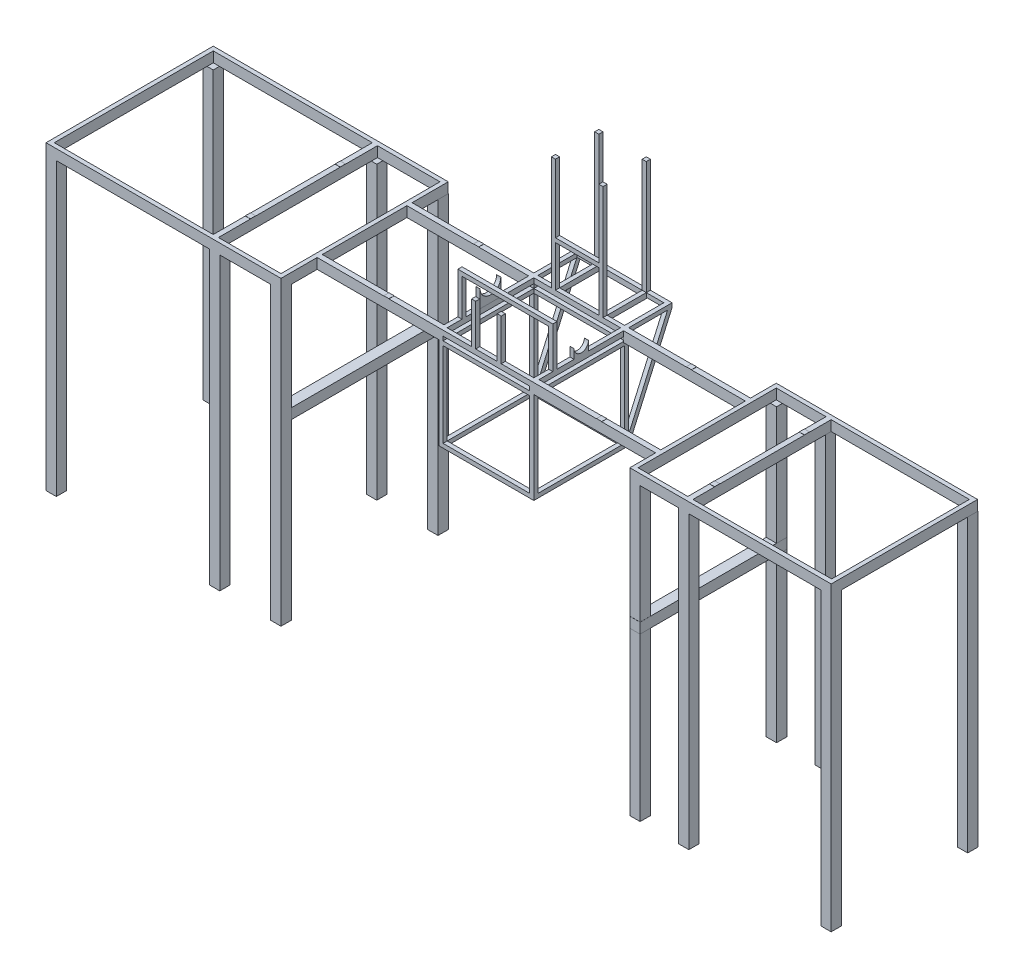
SolidWorks part; units mm, degrees
ref_plane "Front" through (0, 0, 0) normal (0, 0, 1) x (1, 0, 0)
ref_plane "Top" through (0, 0, 0) normal (0, 1, 0) x (1, 0, 0)
ref_plane "Right" through (0, 0, 0) normal (1, 0, 0) x (0, 0, -1)
sketch "Croquis1" plane through (0, 0, 0) normal (0, 1, 0) x (1, 0, 0)
  line L0 (20, 20) -> (440, 20)
  line L1 (0, 0) -> (460, 0)
  line L2 (0, 0) -> (0, 460)
  line L3 (0, 460) -> (460, 460)
  line L4 (460, 0) -> (460, 460)
  line L5 (440, 20) -> (440, 440)
  line L6 (20, 440) -> (440, 440)
  line L7 (20, 20) -> (20, 440)
  dimension "D1" = 20
  dimension "D2" = 420
extrude "Saliente-Extruir1" add sketch "Croquis1" along normal blind 25
sketch "Croquis2" plane through (0, 0, 0) normal (0, -1, 0) x (1, 0, 0)
  line L1 (0, 0) -> (20, 0)
  line L2 (0, 0) -> (0, -20)
  line L3 (0, -20) -> (20, -20)
  line L4 (20, 0) -> (20, -20)
  line L5 (0, -460) -> (20, -460)
  line L6 (0, -460) -> (0, -440)
  line L7 (0, -440) -> (20, -440)
  line L8 (20, -460) -> (20, -440)
  line L9 (460, -460) -> (440, -460)
  line L10 (460, -460) -> (460, -440)
  line L11 (460, -440) -> (440, -440)
  line L12 (440, -460) -> (440, -440)
  line L13 (460, 0) -> (440, 0)
  line L14 (460, 0) -> (460, -20)
  line L15 (460, -20) -> (440, -20)
  line L16 (440, 0) -> (440, -20)
extrude "Saliente-Extruir2" add sketch "Croquis2" along normal blind 20
sketch "Croquis3" plane through (0, -20, 0) normal (0, -1, 0) x (1, 0, 0)
  line L0 (20, -440) -> (20, -20)
  line L1 (0, -460) -> (460, -460)
  line L2 (0, -460) -> (0, 0)
  line L3 (0, 0) -> (460, 0)
  line L4 (460, -460) -> (460, 0)
  line L5 (20, -20) -> (440, -20)
  line L6 (440, -440) -> (440, -20)
  line L7 (20, -440) -> (440, -440)
  dimension "D1" = 20
extrude "Saliente-Extruir3" add sketch "Croquis3" along normal blind 20
sketch "Croquis4" plane through (0, -40, 0) normal (0, -1, 0) x (1, 0, 0)
  line L0 (460, -460) -> (460, 0) construction
  line L1 (0, 0) -> (20, 0)
  line L2 (0, 0) -> (0, -20)
  line L3 (0, -20) -> (20, -20)
  line L4 (20, 0) -> (20, -20)
  line L5 (0, -460) -> (20, -460)
  line L6 (0, -460) -> (0, -440)
  line L7 (0, -440) -> (20, -440)
  line L8 (20, -460) -> (20, -440)
  line L9 (460, -460) -> (440, -460)
  line L10 (460, -460) -> (460, -440)
  line L11 (460, -440) -> (440, -440)
  line L12 (440, -460) -> (440, -440)
  line L13 (460, 0) -> (440, 0)
  line L14 (460, 0) -> (460, -20)
  line L15 (460, -20) -> (440, -20)
  line L16 (440, 0) -> (440, -20)
  line L17 (460, 0) -> (0, 0) construction
extrude "Saliente-Extruir4" add sketch "Croquis4" along normal blind 410
sketch "Croquis5" plane through (0, -450, 0) normal (0, -1, 0) x (1, 0, 0)
  line L0 (20, -440) -> (20, -20)
  line L1 (0, -460) -> (460, -460)
  line L2 (0, -460) -> (0, 0)
  line L3 (0, 0) -> (460, 0)
  line L4 (460, -460) -> (460, 0)
  line L5 (20, -20) -> (440, -20)
  line L6 (440, -440) -> (440, -20)
  line L7 (20, -440) -> (440, -440)
  dimension "D1" = 20
extrude "Saliente-Extruir5" add sketch "Croquis5" along normal blind 20
sketch "Croquis6" plane through (0, -470, 0) normal (0, -1, 0) x (1, 0, 0)
  line L1 (440, -20) -> (20, -20) construction
  line L2 (0, -460) -> (20, -460)
  line L3 (0, -460) -> (0, -440)
  line L4 (0, -440) -> (20, -440)
  line L5 (20, -460) -> (20, -440)
  line L6 (460, -460) -> (440, -460)
  line L7 (460, -460) -> (460, -440)
  line L8 (460, -440) -> (440, -440)
  line L9 (440, -460) -> (440, -440)
  line L10 (460, 0) -> (440, 0)
  line L11 (460, 0) -> (460, -20)
  line L12 (460, -20) -> (440, -20)
  line L13 (440, 0) -> (440, -20)
  line L14 (440, -440) -> (440, -20) construction
  line L16 (0, 0) -> (20, 0)
  line L17 (0, 0) -> (0, -20)
  line L18 (0, -20) -> (20, -20)
  line L19 (20, 0) -> (20, -20)
sketch "Croquis7" plane through (0, 0, 0) normal (-1, 0, 0) x (0, 0, 1)
  line L1 (0, 25) -> (-25, 25)
  line L2 (0, 25) -> (0, -25)
  line L3 (0, -25) -> (-25, -25)
  line L4 (-25, 25) -> (-25, -25)
  line L5 (-230, 0) -> (-230, -450) construction
  line L6 (-440, 0) -> (-20, 0) construction
  line L7 (-20, -450) -> (-440, -450) construction
  line L8 (-435, 25) -> (-435, -25)
  line L9 (-460, -25) -> (-435, -25)
  line L10 (-460, 25) -> (-460, -25)
  line L11 (-460, 25) -> (-435, 25)
  dimension "D1" = 50
  dimension "D2" = 25
extrude "Saliente-Extruir7" add sketch "Croquis7" along normal blind 590
sketch "Croquis8" plane through (460, 0, 0) normal (1, 0, 0) x (0, 0, -1)
  line L0 (230, 25) -> (230, -450) construction
  line L1 (0, 25) -> (25, 25)
  line L2 (0, 25) -> (0, -25)
  line L3 (0, -25) -> (25, -25)
  line L4 (25, 25) -> (25, -25)
  line L5 (0, 25) -> (460, 25) construction
  line L6 (440, -450) -> (20, -450) construction
  line L7 (435, 25) -> (435, -25)
  line L8 (460, -25) -> (435, -25)
  line L9 (460, 25) -> (460, -25)
  line L10 (460, 25) -> (435, 25)
  dimension "D1" = 25
  dimension "D2" = 50
extrude "Saliente-Extruir8" add sketch "Croquis8" along normal blind 590
sketch "Croquis9" plane through (0, 25, 0) normal (0, 1, 0) x (1, 0, 0)
  line L0 (1050, 460) -> (-590, 460) construction
  line L1 (-267, 460) -> (-242, 460)
  line L2 (-267, 460) -> (-267, 435)
  line L3 (-267, 435) -> (-242, 435)
  line L4 (-242, 460) -> (-242, 435)
  line L5 (-590, 435) -> (0, 435) construction
  line L6 (0, 230) -> (-607.3919, 230) construction
  line L7 (0, 435) -> (0, 25) construction
  line L8 (-242, 0) -> (-242, 25)
  line L9 (-267, 25) -> (-242, 25)
  line L10 (-267, 0) -> (-267, 25)
  line L11 (-267, 0) -> (-242, 0)
  line L12 (1050, 435) -> (460, 435) construction
  line L13 (764, 460) -> (789, 460)
  line L14 (764, 460) -> (764, 435)
  line L15 (764, 435) -> (789, 435)
  line L16 (789, 460) -> (789, 435)
  line L17 (1050, 25) -> (460, 25) construction
  line L18 (764, 25) -> (789, 25)
  line L19 (764, 25) -> (764, 0)
  line L20 (764, 0) -> (789, 0)
  line L21 (789, 25) -> (789, 0)
  line L22 (-590, 0) -> (1050, 0) construction
  line L23 (-590, 435) -> (-590, 25) construction
  line L24 (-913, 0) -> (-938, 0)
  line L25 (-913, 0) -> (-913, 25)
  line L26 (-913, 25) -> (-938, 25)
  line L27 (-938, 0) -> (-938, 25)
  line L28 (-938, 460) -> (-938, 435)
  line L29 (-913, 435) -> (-938, 435)
  line L30 (-913, 460) -> (-913, 435)
  line L31 (-913, 460) -> (-938, 460)
  line L32 (1050, 435) -> (1050, 25) construction
  line L33 (1311, 25) -> (1311, 0)
  line L34 (1336, 0) -> (1311, 0)
  line L35 (1336, 25) -> (1336, 0)
  line L36 (1336, 25) -> (1311, 25)
  line L37 (1311, 460) -> (1311, 435)
  line L38 (1336, 435) -> (1311, 435)
  line L39 (1336, 460) -> (1336, 435)
  line L40 (1336, 460) -> (1311, 460)
  dimension "D1" = 25
  dimension "D2" = 323
  dimension "D3" = 25
  dimension "D4" = 25
  dimension "D5" = 261
extrude "Saliente-Extruir9" add sketch "Croquis9" along normal blind 1
sketch "Croquis10" plane through (0, 25, 0) normal (0, 1, 0) x (1, 0, 0)
  line L0 (-1458.4169, 230) -> (1840.1916, 230) construction
  line L1 (-925.5, 435) -> (-925.5, 25) construction
  line L2 (-938, 435) -> (-913, 435) construction
  line L3 (-913, 25) -> (-938, 25) construction
  line L4 (-610, -155.3) -> (-913, -155.3)
  line L6 (1323.5, 435) -> (1323.5, 25) construction
  line L7 (1311, 435) -> (1336, 435) construction
  line L8 (1336, 25) -> (1311, 25) construction
  line L9 (-590, 635.3) -> (-590, -175.3)
  line L10 (-590, -175.3) -> (-1261, -175.3)
  line L11 (-590, 635.3) -> (-1261, 635.3)
  line L13 (-610, 615.3) -> (-913, 615.3)
  line L14 (-610, 615.3) -> (-610, -155.3)
  line L15 (1070, 564.8) -> (1070, -104.8)
  line L16 (1597, 584.8) -> (1050, 584.8)
  line L18 (1597, -124.8) -> (1050, -124.8)
  line L19 (1050, 584.8) -> (1050, -124.8)
  line L20 (1597, 584.8) -> (1050, -124.8) construction
  line L21 (1597, -124.8) -> (1050, 584.8) construction
  line L22 (1577, -104.8) -> (1336, -104.8)
  line L24 (1577, 564.8) -> (1336, 564.8)
  line L25 (-913, 615.3) -> (-913, -155.3)
  line L26 (-938, 615.3) -> (-938, -155.3)
  line L27 (1336, -104.8) -> (1336, 564.8)
  line L28 (1311, 564.8) -> (1311, -104.8)
  line L29 (1311, -104.8) -> (1070, -104.8)
  line L30 (1577, -104.8) -> (1070, -104.8) construction
  line L31 (1311, 564.8) -> (1070, 564.8)
  line L32 (1577, 564.8) -> (1070, 564.8) construction
  line L33 (-938, -155.3) -> (-1241, -155.3)
  line L34 (-610, -155.3) -> (-1241, -155.3) construction
  line L35 (-938, 615.3) -> (-1241, 615.3)
  line L36 (-610, 615.3) -> (-1241, 615.3) construction
  line L37 (-1261, 635.3) -> (-1261, -175.3) construction
  line L38 (-1241, 615.3) -> (-1241, -155.3) construction
  line L39 (-1261, 635.3) -> (-1728.6, 635.3)
  line L40 (-1728.6, 635.3) -> (-1728.6, -175.3)
  line L41 (-1728.6, -175.3) -> (-1261, -175.3)
  line L42 (-1241, -155.3) -> (-1708.6, -155.3)
  line L43 (-1708.6, -155.3) -> (-1708.6, 615.3)
  line L44 (-1708.6, 615.3) -> (-1241, 615.3)
  line L45 (1597, 584.8) -> (1597, -124.8) construction
  line L47 (1577, 564.8) -> (1577, -104.8) construction
  line L48 (1597, -124.8) -> (2025.6, -124.8)
  line L49 (2025.6, -124.8) -> (2025.6, 584.8)
  line L50 (2025.6, 584.8) -> (1597, 584.8)
  line L52 (2005.6, 558.8548) -> (2005.6, -102.5587)
  line L53 (2005.6, -102.5587) -> (1577, -104.8)
  line L54 (1577, 564.8) -> (2005.6, 564.8)
  line L55 (2005.6, 564.8) -> (2005.6, 558.8548)
  point P22 (-590, 230)
  point P24 (-925.5, -175.3)
  point P25 (-925.5, 635.3)
  point P27 (1323.5, 230)
  dimension "D1" = 405.3
  dimension "D2" = 230
  dimension "D3" = 20
  dimension "D4" = 709.6
  dimension "D5" = 547
  dimension "D7" = 20
  dimension "D8" = 770.6
  dimension "D9" = 20
  dimension "D10" = 669.6
  dimension "D6" = 20
extrude "Saliente-Extruir10" add sketch "Croquis10" against normal blind 50
sketch "Croquis11" plane through (0, -25, 0) normal (0, -1, 0) x (1, 0, 0)
  line L5 (-590, 175.3) -> (-640, 175.3)
  line L6 (-590, 175.3) -> (-590, 125.3)
  line L7 (-590, 125.3) -> (-640, 125.3)
  line L8 (-640, 175.3) -> (-640, 125.3)
  line L30 (1050, 124.8) -> (1100, 124.8)
  line L31 (1050, 124.8) -> (1050, 74.8)
  line L32 (1050, 74.8) -> (1100, 74.8)
  line L33 (1100, 124.8) -> (1100, 74.8)
  line L35 (2005.6, -231.1207) -> (-1728.6, -230) construction
  line L36 (2005.6, 102.5587) -> (2005.6, -564.8) construction
  line L37 (-1728.6, -635.3) -> (-1728.6, 175.3) construction
  line L38 (-1728.6, 175.3) -> (-590, 175.3) construction
  line L39 (-1728.6, 175.3) -> (-1678.6, 175.3)
  line L40 (-1728.6, 175.3) -> (-1728.6, 125.3)
  line L41 (-1728.6, 125.3) -> (-1678.6, 125.3)
  line L42 (-1678.6, 175.3) -> (-1678.6, 125.3)
  line L43 (-936.573, 175.3) -> (-886.573, 175.3)
  line L44 (-936.573, 175.3) -> (-936.573, 125.3)
  line L45 (-936.573, 125.3) -> (-886.573, 125.3)
  line L46 (-886.573, 175.3) -> (-886.573, 125.3)
  line L47 (1050, 124.8) -> (2025.6, 124.8) construction
  line L48 (2025.6, 124.8) -> (1975.6, 124.8)
  line L49 (2025.6, 124.8) -> (2025.6, 74.8)
  line L50 (2025.6, 74.8) -> (1975.6, 74.8)
  line L51 (1975.6, 124.8) -> (1975.6, 74.8)
  line L52 (1335.9595, 124.8) -> (1285.9595, 124.8)
  line L53 (1335.9595, 124.8) -> (1335.9595, 74.8)
  line L54 (1335.9595, 74.8) -> (1285.9595, 74.8)
  line L55 (1285.9595, 124.8) -> (1285.9595, 74.8)
  line L56 (1285.746, -586.6093) -> (1285.776, -536.6093)
  line L57 (1335.776, -536.6393) -> (1285.776, -536.6093)
  line L58 (1335.746, -586.6393) -> (1335.776, -536.6393)
  line L59 (1335.746, -586.6393) -> (1285.746, -586.6093)
  line L60 (1975.3864, -587.0232) -> (1975.4164, -537.0233)
  line L61 (2025.4164, -537.0533) -> (1975.4164, -537.0233)
  line L62 (2025.3864, -587.0533) -> (2025.4164, -537.0533)
  line L63 (2025.3864, -587.0533) -> (1975.3864, -587.0232)
  line L64 (-886.8164, -635.8053) -> (-886.7864, -585.8053)
  line L65 (-936.7864, -585.7753) -> (-886.7864, -585.8053)
  line L66 (-936.8164, -635.7753) -> (-936.7864, -585.7753)
  line L67 (-936.8164, -635.7753) -> (-886.8164, -635.8053)
  line L68 (-1678.8433, -635.3299) -> (-1678.8133, -585.3299)
  line L69 (-1728.8133, -585.2999) -> (-1678.8133, -585.3299)
  line L70 (-1728.8433, -635.2999) -> (-1728.8133, -585.2999)
  line L71 (-1728.8433, -635.2999) -> (-1678.8433, -635.3299)
  line L72 (1099.7865, -586.4977) -> (1099.8165, -536.4977)
  line L73 (1049.8166, -536.4677) -> (1099.8165, -536.4977)
  line L74 (1049.7865, -586.4677) -> (1049.8166, -536.4677)
  line L75 (1049.7865, -586.4677) -> (1099.7865, -586.4977)
  line L76 (-640.2435, -635.9533) -> (-640.2135, -585.9533)
  line L77 (-590.2135, -585.9833) -> (-640.2135, -585.9533)
  line L78 (-590.2435, -635.9833) -> (-590.2135, -585.9833)
  line L79 (-590.2435, -635.9833) -> (-640.2435, -635.9533)
  line L84 (-938, -615.3) -> (-938, 155.3) construction
  dimension "D1" = 50
  dimension "D2" = 50
  dimension "D10" = 50
  dimension "D16" = 50
  dimension "D3" = 50
  dimension "D4" = 50
  dimension "D6" = 50
  dimension "D7" = 50
extrude "Saliente-Extruir11" add sketch "Croquis11" along normal blind 1410
sketch "Croquis13" plane through (0, 0, -460) normal (0, 0, -1) x (-1, 0, 0)
  line L0 (-230, -450) -> (-230, -20) construction
  line L2 (-20, -450) -> (-440, -450) construction
  line L3 (-20, -20) -> (-440, -20) construction
  line L4 (-764, 25) -> (242, 25) construction
  line L5 (-335, 25) -> (-355, 25)
  line L6 (-335, 25) -> (-335, 0)
  line L7 (-335, 0) -> (-355, 0)
  line L8 (-355, 25) -> (-355, 0)
  line L9 (-440, 0) -> (-20, 0) construction
  line L10 (-105, 25) -> (-105, 0)
  line L11 (-125, 0) -> (-105, 0)
  line L12 (-125, 25) -> (-125, 0)
  line L13 (-125, 25) -> (-105, 25)
  dimension "D1" = 20
  dimension "D2" = 105
extrude "Saliente-Extruir12" add sketch "Croquis13" along normal blind 210
sketch "Croquis14" plane through (125, 0, 0) normal (1, 0, 0) x (0, 0, -1)
  line L0 (670, 0) -> (460, 0) construction
  line L1 (670, 25) -> (650, 25)
  line L2 (670, 25) -> (670, 0)
  line L3 (670, 0) -> (650, 0)
  line L4 (650, 25) -> (650, 0)
  dimension "D1" = 20
extrude "Saliente-Extruir13" add sketch "Croquis14" along normal up to surface (210 mm away) up to face at (335, 12.5, -565)
sketch "Croquis15" plane through (0, 25, 0) normal (0, 1, 0) x (1, 0, 0)
  line L0 (230, 20) -> (230, 165.9322) construction
  line L1 (20, 20) -> (440, 20) construction
  line L2 (-242, 0) -> (764, 0) construction
  line L3 (302, 0) -> (282, 0)
  line L4 (302, 0) -> (302, 20)
  line L5 (302, 20) -> (282, 20)
  line L6 (282, 0) -> (282, 20)
  line L7 (178, 0) -> (178, 20)
  line L8 (158, 20) -> (178, 20)
  line L9 (158, 0) -> (158, 20)
  line L10 (158, 0) -> (178, 0)
  dimension "D1" = 20
  dimension "D2" = 52
extrude "Saliente-Extruir14" add sketch "Croquis15" along normal blind 200
sketch "Croquis16" plane through (0, 25, 0) normal (0, 1, 0) x (1, 0, 0)
  line L0 (440, 440) -> (20, 440) construction
  line L1 (355, 670) -> (335, 670)
  line L2 (355, 670) -> (355, 650)
  line L3 (355, 650) -> (335, 650)
  line L4 (335, 670) -> (335, 650)
  line L5 (105, 670) -> (125, 670)
  line L6 (105, 670) -> (105, 650)
  line L7 (105, 650) -> (125, 650)
  line L8 (125, 670) -> (125, 650)
  line L9 (335, 460) -> (355, 460)
  line L10 (335, 460) -> (335, 440)
  line L11 (335, 440) -> (355, 440)
  line L12 (355, 460) -> (355, 440)
  line L14 (125, 460) -> (105, 460)
  line L15 (125, 460) -> (125, 440)
  line L16 (125, 440) -> (105, 440)
  line L17 (105, 460) -> (105, 440)
extrude "Saliente-Extruir15" add sketch "Croquis16" along normal blind 550
sketch "Croquis17" plane through (0, 25, 0) normal (0, 1, 0) x (1, 0, 0)
  line L1 (0, 440) -> (460, 440)
  line L2 (0, 440) -> (0, 670)
  line L3 (0, 670) -> (460, 670)
  line L4 (460, 440) -> (460, 670)
  line L5 (20, 460) -> (440, 460)
  line L6 (20, 460) -> (20, 650)
  line L7 (20, 650) -> (440, 650)
  line L8 (440, 460) -> (440, 650)
extrude "Saliente-Extruir16" add sketch "Croquis17" against normal blind 20
sketch "Croquis18" plane through (0, 0, 0) normal (-1, 0, 0) x (0, 0, 1)
  line L0 (-670, 5) -> (-460, -470)
  line L1 (-651.7079, 13.087) -> (-441.7079, -461.913)
  line L2 (-460, -470) -> (-441.7079, -461.913)
  line L3 (-670, 5) -> (-651.7079, 13.087)
  dimension "D1" = 20
extrude "Saliente-Extruir17" add sketch "Croquis18" against normal blind 20
sketch "Croquis19" plane through (460, 0, 0) normal (1, 0, 0) x (0, 0, -1)
  line L0 (670, 5) -> (460, -470)
  line L1 (651.7079, 13.087) -> (441.7079, -461.913)
  line L2 (460, -470) -> (441.7079, -461.913)
  line L3 (670, 5) -> (651.7079, 13.087)
  dimension "D1" = 20
extrude "Saliente-Extruir18" add sketch "Croquis19" against normal blind 20
sketch "Croquis23" plane through (0, 25, 0) normal (0, 1, 0) x (1, 0, 0)
  line L0 (0, 435) -> (0, 25) construction
  line L1 (0, 92) -> (20, 92)
  line L2 (0, 92) -> (0, 112)
  line L3 (0, 112) -> (20, 112)
  line L4 (20, 92) -> (20, 112)
  line L5 (20, 440) -> (20, 20) construction
  line L6 (440, 20) -> (440, 440) construction
  line L7 (440, 92) -> (460, 92)
  line L8 (440, 92) -> (440, 112)
  line L9 (440, 112) -> (460, 112)
  line L10 (460, 92) -> (460, 112)
  line L11 (460, 25) -> (460, 435) construction
  line L13 (302, 0) -> (764, 0) construction
  line L14 (-242, 0) -> (158, 0) construction
  dimension "D1" = 20
  dimension "D2" = 20
  dimension "D3" = 20
  dimension "D4" = 112
  dimension "D5" = 112
extrude "Saliente-Extruir22" add sketch "Croquis23" along normal blind 200
sketch "Croquis24" plane through (440, 0, 0) normal (-1, 0, 0) x (0, 0, 1)
  line L0 (-92, 225) -> (-92, 25) construction
  line L1 (-112, 225) -> (-92, 225)
  line L2 (-112, 225) -> (-112, 205)
  line L3 (-112, 205) -> (-92, 205)
  line L4 (-92, 225) -> (-92, 205)
  dimension "D1" = 20
extrude "Saliente-Extruir23" add sketch "Croquis24" along normal up to surface (420 mm away) up to face at (20, 68.75, -166)
sketch "Croquis25" plane through (-0.3519, 0, -586.3374) normal (0.0006, 0, 1) x (1, 0, -0.0006)
  line L1 (-640.4028, -543.4336) -> (-590.4028, -543.4336)
  line L2 (-640.4028, -543.4336) -> (-640.4028, -593.4336)
  line L3 (-640.4028, -593.4336) -> (-590.4028, -593.4336)
  line L4 (-590.4028, -543.4336) -> (-590.4028, -593.4336)
  line L5 (1100.2012, -597.872) -> (1050.2012, -597.872)
  line L6 (1100.2012, -597.872) -> (1100.2012, -647.872)
  line L7 (1100.2012, -647.872) -> (1050.2012, -647.872)
  line L8 (1050.2012, -597.872) -> (1050.2012, -647.872)
  dimension "D1" = 50
  dimension "D2" = 50
  dimension "D3" = 50
  dimension "D4" = 50
  dimension "D5" = 787.128
extrude "Saliente-Extruir24" add sketch "Croquis25" along normal up to surface (711.2831 mm away)
sketch "Croquis27" plane through (0, 0, 0) normal (-1, 0, 0) x (0, 0, 1)
  line L0 (175.3, 25) -> (-180, 25) construction
  line L2 (-180, 25) -> (-180, 108)
  line L5 (-280, 108) -> (-280, 25)
  line L10 (-280, 25) -> (-635.3, 25) construction
  line L11 (-180, 25) -> (-280, 25)
  line L12 (-230, 25) -> (-230, 108) construction
  arc A0 (-280, 108) -> (-180, 108) centre (-230, 108) ccw
  dimension "D1" = 83
extrude "Saliente-Extruir25" add sketch "Croquis27" against normal blind 20 separate body
sketch "Croquis28" plane through (460, 0, 0) normal (1, 0, 0) x (0, 0, -1)
  line L0 (-124.8, 25) -> (195, 25) construction
  line L2 (195, 25) -> (195, 70)
  line L5 (265, 70) -> (265, 25)
  line L10 (265, 25) -> (584.8, 25) construction
  line L11 (195, 25) -> (265, 25)
  arc A0 (195, 70) -> (265, 70) centre (230, 70) ccw
  dimension "D1" = 45
extrude "Saliente-Extruir26" add sketch "Croquis28" against normal blind 20
sketch "Croquis29" plane through (125, 0, 0) normal (1, 0, 0) x (0, 0, -1)
  line L0 (440, 575) -> (440, 25) construction
  line L1 (440, 245) -> (460, 245)
  line L2 (440, 245) -> (440, 225)
  line L3 (440, 225) -> (460, 225)
  line L4 (460, 245) -> (460, 225)
  line L5 (460, 575) -> (460, 25) construction
  line L6 (440, 25) -> (460, 25) construction
  dimension "D1" = 20
  dimension "D2" = 200
extrude "Saliente-Extruir27" add sketch "Croquis29" along normal up to next
equation "\"Alto\"= 50mm"
equation "\"Ancho\"= \"Alto\" / 2"
equation "\"D2@Croquis8\"=\"Alto\""
equation "\"D1@Croquis9\"=\"Ancho\""
equation "\"D3@Croquis9\"=\"Ancho\""
equation "\"D4@Croquis9\"=\"Ancho\""
equation "\"D10@Croquis11\"=\"Alto\""
